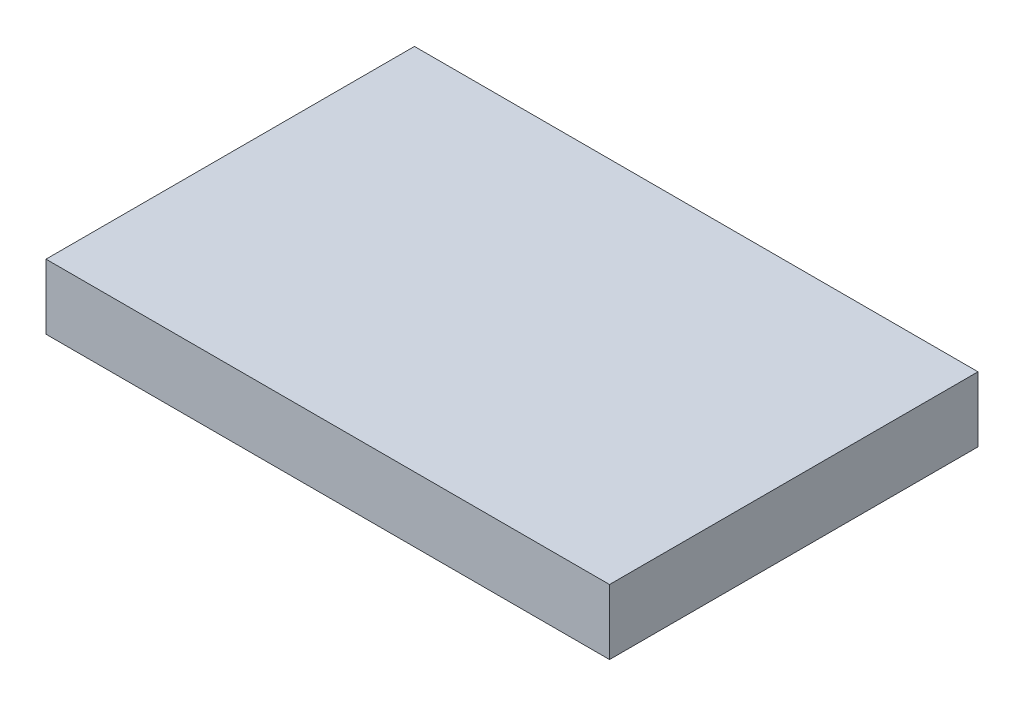
SolidWorks part; units mm, degrees
ref_plane "Front Plane" through (0, 0, 0) normal (0, 0, 1) x (1, 0, 0)
ref_plane "Top Plane" through (0, 0, 0) normal (0, 1, 0) x (1, 0, 0)
ref_plane "Right Plane" through (0, 0, 0) normal (1, 0, 0) x (0, 0, -1)
sketch "Sketch1" plane through (0, 0, 0) normal (0, 1, 0) x (1, 0, 0)
  line L1 (-33.364, 21.8414) -> (49.186, 21.8414)
  line L2 (-33.364, 21.8414) -> (-33.364, -32.1336)
  line L3 (-33.364, -32.1336) -> (49.186, -32.1336)
  line L4 (49.186, 21.8414) -> (49.186, -32.1336)
  dimension "D1" = 82.55
  dimension "D2" = 53.975
extrude "Boss-Extrude1" add sketch "Sketch1" along normal blind 9.525
